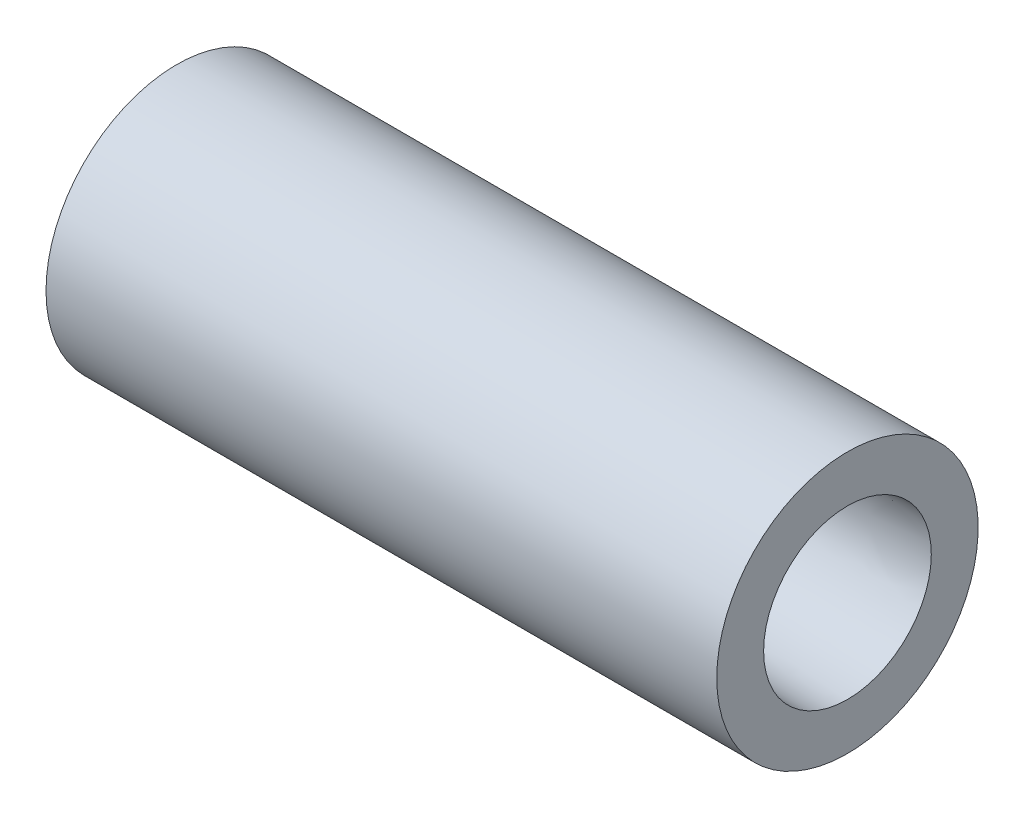
SolidWorks part; units mm, degrees
material "201 Tavlı Paslanmaz Çelik (SS)"
ref_plane "Ön Düzlem" through (0, 0, 0) normal (0, 0, 1) x (1, 0, 0)
ref_plane "Üst Düzlem" through (0, 0, 0) normal (0, 1, 0) x (1, 0, 0)
ref_plane "Sağ Düzlem" through (0, 0, 0) normal (1, 0, 0) x (0, 0, -1)
sketch "Çizim1" plane through (0, 0, 0) normal (0, 0, 1) x (1, 0, 0)
  line L0 (0, 3.5792) -> (0, 5.5792)
  line L1 (0, 5.5792) -> (28.6336, 5.5792)
  line L2 (28.6336, 5.5792) -> (28.6336, 3.5792)
  line L3 (0, 0) -> (28.6336, 0) construction
  spline S0 degree 2 poles (28.6336, 3.5792) (27.2888, 3.5488) (25.9457, 3.4884) (24.7485, 3.4345) (23.2607, 3.3397) (22.1681, 3.27) (20.5772, 3.16) (18.9727, 3.0491) (17.896, 2.9528) knots 0 0 0 0.25 0.25 0.5 0.5 0.75 0.75 1 1 1
  spline S1 degree 2 poles (17.896, 2.9528) (17.0169, 2.8742) (16.105, 2.7778) (15.2096, 2.6831) (14.314, 2.5908) (13.2797, 2.4842) (12.5235, 2.4156) (11.8721, 2.3565) (11.6298, 2.3288) (11.1288, 2.2715) (10.7376, 2.1923) knots 0 0 0 0.25 0.25 0.5 0.5 0.75 0.75 0.875 0.875 1 1 1
  spline S2 degree 2 poles (10.7376, 2.1923) (10.7141, 2.1875) (10.5126, 2.1448) (10.3759, 2.1159) (10.2877, 2.1002) (10.0299, 2.0544) (9.839, 2.0581) (9.6417, 2.0619) (9.3921, 2.1184) (9.3231, 2.134) (9.2437, 2.1548) (9.1724, 2.1734) (8.948, 2.237) knots 0 0 0 0.125 0.125 0.25 0.25 0.5 0.5 0.75 0.75 0.833333 0.833333 1 1 1
  spline S3 degree 2 poles (8.948, 2.237) (8.6111, 2.3324) (8.2778, 2.4194) (7.9442, 2.5064) (7.6107, 2.5936) (7.039, 2.7431) (6.2734, 2.9502) (5.2966, 3.2144) (4.9362, 3.307) (4.5234, 3.413) (4.2612, 3.4683) (3.8889, 3.5468) (3.5792, 3.5792) knots 0 0 0 0.125 0.125 0.25 0.25 0.5 0.5 0.75 0.75 0.875 0.875 1 1 1
  spline S4 degree 2 poles (3.5792, 3.5792) (3.1989, 3.6189) (2.6869, 3.6101) (2.4623, 3.6062) (2.2383, 3.5966) (2.014, 3.5869) (1.7896, 3.5792) (0.8925, 3.5483) (0, 3.5792) knots 0 0 0 0.25 0.25 0.375 0.375 0.5 0.5 1 1 1
  point P9 (0, 0)
  dimension "D1" = 2
revolve "Döndür1" add sketch "Çizim1" angle 360 about L3
